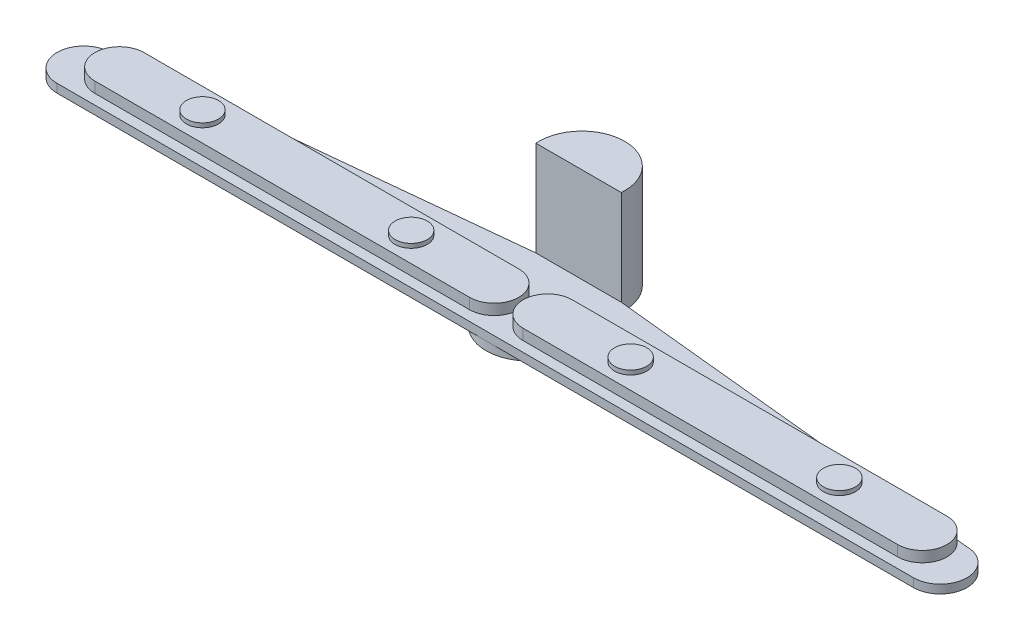
SolidWorks part; units mm, degrees
material "Ductile Iron"
ref_plane "Front Plane" through (0, 0, 0) normal (0, 0, 1) x (1, 0, 0)
ref_plane "Top Plane" through (0, 0, 0) normal (0, 1, 0) x (1, 0, 0)
ref_plane "Right Plane" through (0, 0, 0) normal (1, 0, 0) x (0, 0, -1)
sketch "Sketch1" plane through (0, 0, 0) normal (0, 1, 0) x (1, 0, 0)
  line L2 (-1446.8954, -407.2331) -> (2553.1046, -407.2331) construction
  line L5 (-1446.8954, -532.2331) -> (2553.1046, -532.2331)
  line L6 (-1438.6392, -282.5061) -> (357.7568, -100.2293)
  line L7 (2553.0605, -282.2331) -> (756.6368, -100.2293)
  arc A8 (756.6368, -100.2293) -> (357.7568, -100.2293) centre (557.1968, -85.2731) ccw
  arc A9 (2553.1046, -532.2331) -> (2553.0605, -282.2331) centre (2553.1046, -407.2331) ccw
  arc A10 (-1438.6392, -282.5061) -> (-1446.8954, -532.2331) centre (-1446.8954, -407.2331) ccw
  dimension "D4" = 4000
  dimension "D5" = 1805.62
  dimension "D6" = 1805.62
  dimension "D8" = 400
  dimension "D1" = 446.96
  dimension "D2" = 250
  dimension "D9" = 250
  dimension "D3" = 4000
  dimension "D7" = 398.88
extrude "Boss-Extrude1" add sketch "Sketch1" along normal blind 40
sketch "Sketch2" plane through (0, 40, 0) normal (0, 1, 0) x (1, 0, 0)
  line L0 (-1317.8032, -369.7331) -> (432.1968, -369.7331) construction
  line L1 (682.1968, -369.7331) -> (2432.1968, -369.7331) construction
  line L2 (-1446.8954, -532.2331) -> (2553.1046, -532.2331) construction
  line L3 (557.1968, 114.7269) -> (557.1968, -532.2331) construction
  line L4 (682.1968, -254.7331) -> (2432.1968, -254.7331)
  line L5 (682.1968, -484.7331) -> (2432.1968, -484.7331)
  line L6 (432.1968, -484.7331) -> (-1317.8032, -484.7331)
  line L7 (357.7568, -100.2293) -> (756.6368, -100.2293) construction
  line L8 (-1317.8032, -254.7331) -> (432.1968, -254.7331)
  arc A0 (2432.1968, -484.7331) -> (2432.1968, -254.7331) centre (2432.1968, -369.7331) ccw
  arc A1 (682.1968, -254.7331) -> (682.1968, -484.7331) centre (682.1968, -369.7331) ccw
  arc A2 (432.1968, -484.7331) -> (432.1968, -254.7331) centre (432.1968, -369.7331) ccw
  arc A3 (-1317.8032, -254.7331) -> (-1317.8032, -484.7331) centre (-1317.8032, -369.7331) ccw
  point P6 (557.1968, -208.7531)
  dimension "D1" = 230
  dimension "D2" = 1750
  dimension "D3" = 1750
  dimension "D4" = 162.5
  dimension "D5" = 250
  dimension "D6" = 125
  dimension "D7" = 1750
  dimension "D8" = 1750
extrude "Boss-Extrude2" add sketch "Sketch2" along normal blind 50
sketch "Sketch3" plane through (0, 90, 0) normal (0, 1, 0) x (1, 0, 0)
  line L0 (357.7568, -100.2293) -> (756.6368, -100.2293) construction
  line L1 (-930.3032, -369.7331) -> (44.6968, -369.7331) construction
  line L2 (44.6968, -369.7331) -> (1069.6968, -369.7331) construction
  line L3 (1069.6968, -369.7331) -> (2044.6968, -369.7331) construction
  line L4 (557.1968, 114.7269) -> (557.1968, -369.7331) construction
  line L6 (2432.1968, -254.7331) -> (682.1968, -254.7331) construction
  circle A0 centre (-930.3032, -369.7331) radius 75
  circle A1 centre (44.6968, -369.7331) radius 75
  circle A2 centre (1069.6968, -369.7331) radius 75
  circle A3 centre (2044.6968, -369.7331) radius 75
  point P14 (557.1968, -100.2293)
  dimension "D1" = 150
  dimension "D2" = 975
  dimension "D3" = 975
  dimension "D4" = 1025
  dimension "D5" = 512.5
  dimension "D6" = 115
extrude "Boss-Extrude3" add sketch "Sketch3" along normal blind 20
sketch "Sketch4" plane through (0, 0, 0) normal (0, -1, 0) x (-1, 0, 0)
  line L0 (-557.1968, 114.7269) -> (-557.1968, -532.2331) construction
  line L1 (1446.8954, -532.2331) -> (-2553.1046, -532.2331) construction
  circle A1 centre (-557.1968, -332.2331) radius 200
  dimension "D1" = 400
  dimension "D2" = 200
extrude "Boss-Extrude4" add sketch "Sketch4" along normal blind 40
sketch "Sketch5" plane through (0, 40, 0) normal (0, 1, 0) x (1, 0, 0)
  line L0 (756.6368, -100.2293) -> (357.7568, -100.2293)
  line L1 (357.7568, -100.2293) -> (-1164.9279, -254.7331) construction
  arc A0 (756.6368, -100.2293) -> (357.7568, -100.2293) centre (557.1968, -85.2731) ccw
extrude "Boss-Extrude5" add sketch "Sketch5" along normal blind 444
